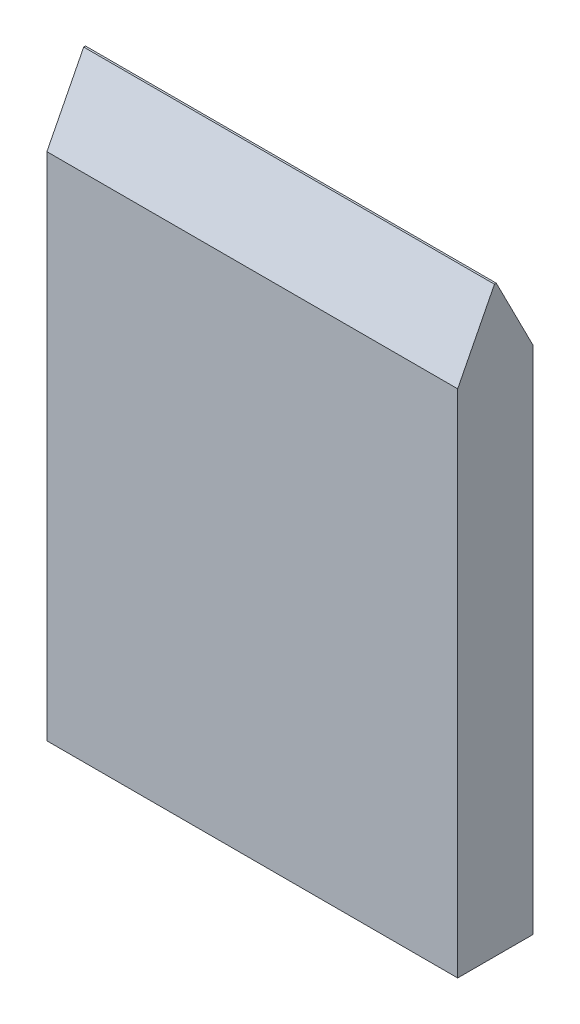
SolidWorks part; units mm, degrees
ref_plane "Front Plane" through (0, 0, 0) normal (0, 0, 1) x (1, 0, 0)
ref_plane "Top Plane" through (0, 0, 0) normal (0, 1, 0) x (1, 0, 0)
ref_plane "Right Plane" through (0, 0, 0) normal (1, 0, 0) x (0, 0, -1)
sketch "Sketch1" plane through (0, 0, 0) normal (0, 0, 1) x (1, 0, 0)
  line L1 (3.35, -4.75) -> (-3.35, -4.75)
  line L2 (3.35, -4.75) -> (3.35, 4.75)
  line L3 (3.35, 4.75) -> (-3.35, 4.75)
  line L4 (-3.35, -4.75) -> (-3.35, 4.75)
  line L5 (0, 4.75) -> (0, -4.75) construction
  line L6 (3.35, 0) -> (-3.35, 0) construction
  point P0 (0, 0)
  dimension "D1" = 9.5
  dimension "D2" = 6.7
extrude "Boss-Extrude1" add sketch "Sketch1" along normal blind 1.23
chamfer "Chamfer1" distance 0.6 angle 63 2 edges at (0, 4.75, 0) (0, 4.75, 1.23)
